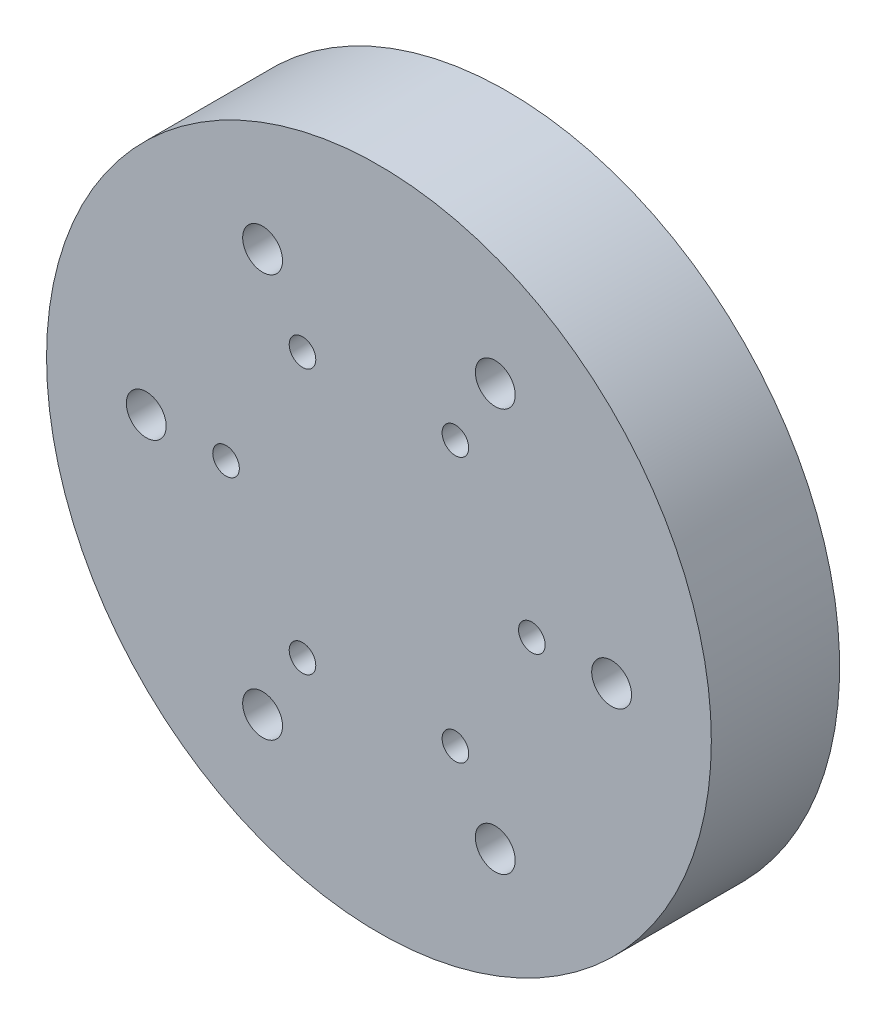
SolidWorks part; units mm, degrees
ref_plane "前视基准面" through (0, 0, 0) normal (0, 0, 1) x (1, 0, 0)
ref_plane "上视基准面" through (0, 0, 0) normal (0, 1, 0) x (1, 0, 0)
ref_plane "右视基准面" through (0, 0, 0) normal (1, 0, 0) x (0, 0, -1)
sketch "草图1" plane through (0, 0, 0) normal (0, 0, 1) x (1, 0, 0)
  circle A0 centre (0, 0) radius 50
  circle A1 centre (0, 0) radius 35
  circle A2 centre (-35, 0) radius 3
  circle A3 centre (-17.5, 30.3109) radius 3
  circle A4 centre (17.5, 30.3109) radius 3
  circle A5 centre (35, 0) radius 3
  circle A6 centre (17.5, -30.3109) radius 3
  circle A7 centre (-17.5, -30.3109) radius 3
  circle A8 centre (0, 0) radius 23
  circle A9 centre (-23, 0) radius 2
  circle A10 centre (-11.5, 19.9186) radius 2
  circle A11 centre (11.5, 19.9186) radius 2
  circle A12 centre (23, 0) radius 2
  circle A13 centre (11.5, -19.9186) radius 2
  circle A14 centre (-11.5, -19.9186) radius 2
  point P18 (0, 0)
  point P32 (0, 0)
  dimension "D1" = 100
  dimension "D2" = 70
  dimension "D3" = 6
  dimension "D4" = 46
  dimension "D5" = 6
extrude "凸台-拉伸1" add sketch "草图1" along normal blind 20 contours A0 A7 A1 A2 A3 A4 A5 A6 | A7 A1 A6 A5 A4 A3 A2 A14 A8 A9 A10 A11 A12 A13 | A14 A8 A13 A12 A11 A10 A9
sketch "草图3" plane through (0, 0, 20) normal (0, 0, 1) x (1, 0, 0)
  circle A0 centre (0, 0) radius 82.2327
extrude "切除-拉伸1" cut sketch "草图3" against normal blind 10
sketch "草图4" plane through (0, 0, 0) normal (0, 0, -1) x (-1, 0, 0)
  circle A0 centre (0, 0) radius 50
extrude "凸台-拉伸2" add sketch "草图4" along normal blind 9.3
sketch "草图5" plane through (0, 0, 10) normal (0, 0, 1) x (1, 0, 0)
  circle A0 centre (-23, 0) radius 2
  circle A1 centre (-35, 0) radius 3
  circle A2 centre (-17.5, 30.3109) radius 3
  circle A3 centre (-11.5, 19.9186) radius 2
  circle A4 centre (17.5, 30.3109) radius 3
  circle A5 centre (11.5, 19.9186) radius 2
  circle A6 centre (35, 0) radius 3
  circle A7 centre (23, 0) radius 2
  circle A8 centre (17.5, -30.3109) radius 3
  circle A9 centre (11.5, -19.9186) radius 2
  circle A10 centre (-17.5, -30.3109) radius 3
  circle A11 centre (-11.5, -19.9186) radius 2
  point P29 (0, 0)
  circle M4 centre (-23, 0) radius 2
  circle M9 centre (-35, 0) radius 3
  dimension "D1" = 6
extrude "切除-拉伸2" cut sketch "草图5" against normal blind 52 contours M9 | M4
pattern_circular "阵列(圆周)1" count 6 every 60 about axis through (0, 0, 20) along (0, 0, -1) of "切除-拉伸2"
